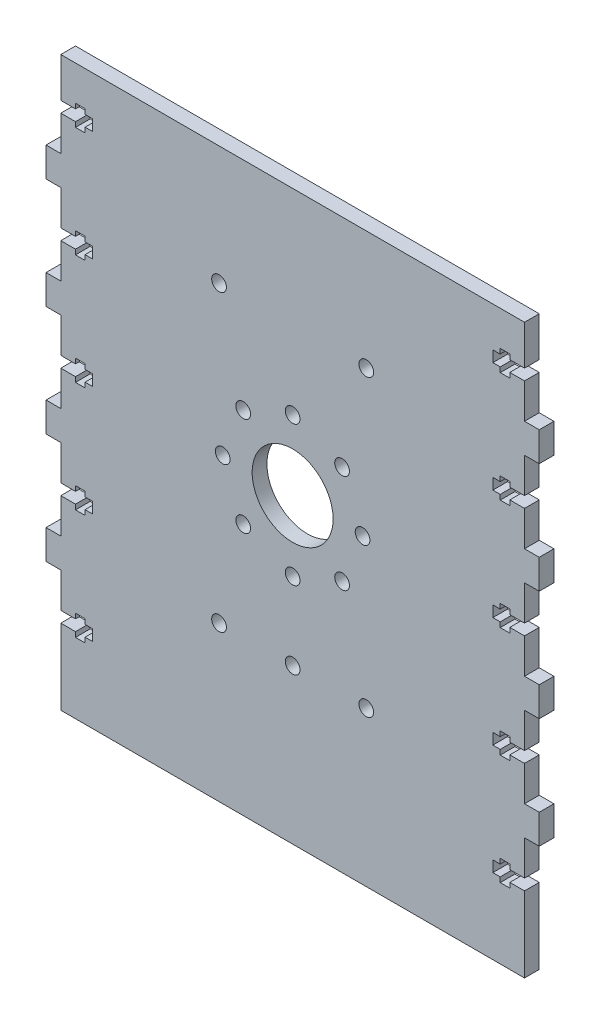
SolidWorks part; units mm, degrees
ref_plane "前视基准面" through (0, 0, 0) normal (0, 0, 1) x (1, 0, 0)
ref_plane "上视基准面" through (0, 0, 0) normal (0, 1, 0) x (1, 0, 0)
ref_plane "右视基准面" through (0, 0, 0) normal (1, 0, 0) x (0, 0, -1)
sketch "草图1" plane through (0, 0, 0) normal (0, 0, 1) x (1, 0, 0)
  line L9 (145, 46.5) -> (149, 46.5)
  line L10 (149, 46.5) -> (149, 45.15)
  line L11 (149, 45.15) -> (151.6, 45.15)
  line L12 (151.6, 45.15) -> (151.6, 46.5)
  line L13 (151.6, 46.5) -> (153.6, 46.5)
  line L14 (153.6, 46.5) -> (153.6, 49.5)
  line L23 (145, 48) -> (143.6922, 48) construction
  line L24 (145, 46.5) -> (145, 49.5) construction
  line L25 (151.6, 50.85) -> (151.6, 49.5)
  line L26 (149, 49.5) -> (149, 50.85)
  line L27 (151.6, 49.5) -> (153.6, 49.5)
  line L28 (149, 50.85) -> (151.6, 50.85)
  line L29 (145, 49.5) -> (149, 49.5)
  line L31 (145, 29) -> (141, 29)
  line L32 (141, 29) -> (141, 37)
  line L33 (141, 37) -> (145, 37)
  line L34 (145, 37) -> (145, 46.5)
  line L35 (141, 33) -> (142.703, 33) construction
  line L43 (149, 15.15) -> (151.6, 15.15)
  line L44 (151.6, 16.5) -> (153.6, 16.5)
  line L45 (149, 16.5) -> (149, 15.15)
  line L69 (262.4, 48) -> (153.6, 48) construction
  line L70 (151.6, 15.15) -> (151.6, 16.5)
  line L71 (153.6, 19.5) -> (153.6, 16.5)
  line L72 (151.6, 19.5) -> (153.6, 19.5)
  line L73 (151.6, 20.85) -> (151.6, 19.5)
  line L98 (149, 20.85) -> (151.6, 20.85)
  line L123 (149, 19.5) -> (149, 20.85)
  line L124 (145, 7) -> (145, 16.5)
  line L125 (149, 16.5) -> (145, 16.5)
  line L126 (149, 19.5) -> (145, 19.5)
  line L127 (145, 19.5) -> (145, 29)
  line L128 (153.6, 18) -> (150.6786, 18) construction
  line L129 (141, 3) -> (142.703, 3) construction
  line L130 (141, -1) -> (145, -1)
  line L131 (141, 7) -> (141, -1)
  line L132 (145, 7) -> (141, 7)
  line L133 (145, -1) -> (145, -10.5)
  line L134 (149, -10.5) -> (145, -10.5)
  line L135 (149, -13.5) -> (145, -13.5)
  line L136 (153.6, -12) -> (150.6786, -12) construction
  line L137 (149, -13.5) -> (149, -14.85)
  line L138 (149, -14.85) -> (151.6, -14.85)
  line L139 (151.6, -14.85) -> (151.6, -13.5)
  line L140 (151.6, -13.5) -> (153.6, -13.5)
  line L141 (153.6, -13.5) -> (153.6, -10.5)
  line L142 (151.6, -9.15) -> (151.6, -10.5)
  line L143 (149, -10.5) -> (149, -9.15)
  line L144 (151.6, -10.5) -> (153.6, -10.5)
  line L145 (149, -9.15) -> (151.6, -9.15)
  line L146 (153.6, 108) -> (150.6786, 108) construction
  line L147 (141, 93) -> (142.703, 93) construction
  line L148 (153.6, 78) -> (150.6786, 78) construction
  line L149 (141, 63) -> (142.703, 63) construction
  line L150 (145, 46.5) -> (149, 46.5)
  line L151 (149, 46.5) -> (149, 45.15)
  line L152 (149, 45.15) -> (151.6, 45.15)
  line L153 (151.6, 45.15) -> (151.6, 46.5)
  line L154 (151.6, 46.5) -> (153.6, 46.5)
  line L155 (151.6, 50.85) -> (151.6, 49.5)
  line L156 (149, 49.5) -> (149, 50.85)
  line L157 (151.6, 49.5) -> (153.6, 49.5)
  line L158 (145, 46.5) -> (149, 46.5)
  line L159 (149, 45.15) -> (151.6, 45.15)
  line L160 (151.6, 46.5) -> (153.6, 46.5)
  line L161 (149, 46.5) -> (149, 45.15)
  line L162 (151.6, 45.15) -> (151.6, 46.5)
  line L163 (151.6, 49.5) -> (153.6, 49.5)
  line L164 (151.6, 50.85) -> (151.6, 49.5)
  line L165 (149, 50.85) -> (151.6, 50.85)
  line L166 (149, 49.5) -> (149, 50.85)
  line L167 (145, 49.5) -> (149, 49.5)
  line L168 (149, 50.85) -> (151.6, 50.85)
  line L169 (145, 49.5) -> (149, 49.5)
  line L170 (149, 105.15) -> (151.6, 105.15)
  line L171 (151.6, 106.5) -> (153.6, 106.5)
  line L172 (149, 106.5) -> (149, 105.15)
  line L173 (151.6, 105.15) -> (151.6, 106.5)
  line L174 (153.6, 109.5) -> (153.6, 106.5)
  line L175 (151.6, 109.5) -> (153.6, 109.5)
  line L177 (151.6, 110.85) -> (151.6, 109.5)
  line L178 (149, 110.85) -> (151.6, 110.85)
  line L179 (149, 109.5) -> (149, 110.85)
  line L180 (149, 109.5) -> (145, 109.5)
  line L181 (149, 106.5) -> (145, 106.5)
  line L182 (145, 97) -> (145, 106.5)
  line L183 (145, 89) -> (141, 89)
  line L184 (141, 89) -> (141, 97)
  line L185 (141, 97) -> (145, 97)
  line L186 (145, 76.5) -> (145, 67)
  line L187 (149, 76.5) -> (145, 76.5)
  line L188 (149, 79.5) -> (145, 79.5)
  line L189 (145, 89) -> (145, 79.5)
  line L190 (149, 76.5) -> (149, 75.15)
  line L191 (149, 75.15) -> (151.6, 75.15)
  line L192 (151.6, 75.15) -> (151.6, 76.5)
  line L193 (151.6, 76.5) -> (153.6, 76.5)
  line L194 (153.6, 76.5) -> (153.6, 79.5)
  line L195 (151.6, 80.85) -> (151.6, 79.5)
  line L196 (149, 79.5) -> (149, 80.85)
  line L197 (151.6, 79.5) -> (153.6, 79.5)
  line L198 (149, 80.85) -> (151.6, 80.85)
  line L199 (145, 59) -> (145, 49.5)
  line L200 (141, 59) -> (145, 59)
  line L201 (141, 67) -> (141, 59)
  line L202 (145, 67) -> (141, 67)
  line L203 (145, 46.5) -> (149, 46.5)
  line L204 (149, 45.15) -> (151.6, 45.15)
  line L205 (151.6, 46.5) -> (153.6, 46.5)
  line L206 (149, 46.5) -> (149, 45.15)
  line L207 (151.6, 45.15) -> (151.6, 46.5)
  line L208 (151.6, 49.5) -> (153.6, 49.5)
  line L209 (151.6, 50.85) -> (151.6, 49.5)
  line L210 (149, 50.85) -> (151.6, 50.85)
  line L211 (149, 49.5) -> (149, 50.85)
  line L212 (145, 49.5) -> (149, 49.5)
  line L213 (275, 63) -> (273.297, 63) construction
  line L214 (262.4, 78) -> (265.3214, 78) construction
  line L215 (275, 93) -> (273.297, 93) construction
  line L216 (262.4, 108) -> (265.3214, 108) construction
  line L217 (262.4, -12) -> (265.3214, -12) construction
  line L218 (275, 3) -> (273.297, 3) construction
  line L219 (262.4, 18) -> (265.3214, 18) construction
  line L220 (275, 33) -> (273.297, 33) construction
  line L221 (271, 46.5) -> (271, 49.5) construction
  line L222 (271, 48) -> (272.3078, 48) construction
  line L223 (271, -27) -> (271, -13.5)
  line L224 (271, 123) -> (271, 109.5)
  line L225 (271, -27) -> (271, -34)
  line L227 (271, 49.5) -> (267, 49.5)
  line L228 (267, 49.5) -> (267, 50.85)
  line L229 (267, 50.85) -> (264.4, 50.85)
  line L230 (264.4, 50.85) -> (264.4, 49.5)
  line L231 (264.4, 49.5) -> (262.4, 49.5)
  line L232 (264.4, 45.15) -> (264.4, 46.5)
  line L233 (267, 46.5) -> (267, 45.15)
  line L234 (264.4, 46.5) -> (262.4, 46.5)
  line L235 (267, 45.15) -> (264.4, 45.15)
  line L253 (271, 46.5) -> (267, 46.5)
  line L254 (271, 67) -> (275, 67)
  line L255 (145, -27) -> (145, -34)
  line L256 (208, 48) -> (208, 8) construction
  line L257 (208, 8) -> (188, 8) construction
  line L258 (275, 67) -> (275, 59)
  line L259 (275, 59) -> (271, 59)
  line L260 (271, 59) -> (271, 49.5)
  line L261 (267, 80.85) -> (264.4, 80.85)
  line L262 (264.4, 79.5) -> (262.4, 79.5)
  line L263 (267, 79.5) -> (267, 80.85)
  line L264 (264.4, 80.85) -> (264.4, 79.5)
  line L265 (262.4, 76.5) -> (262.4, 79.5)
  line L267 (264.4, 76.5) -> (262.4, 76.5)
  line L269 (264.4, 75.15) -> (264.4, 76.5)
  line L270 (267, 75.15) -> (264.4, 75.15)
  line L272 (267, 76.5) -> (267, 75.15)
  line L273 (271, 89) -> (271, 79.5)
  line L274 (267, 79.5) -> (271, 79.5)
  line L275 (267, 76.5) -> (271, 76.5)
  line L277 (271, 76.5) -> (271, 67)
  line L278 (275, 97) -> (271, 97)
  line L279 (275, 89) -> (275, 97)
  line L280 (271, 89) -> (275, 89)
  line L281 (271, 97) -> (271, 106.5)
  line L282 (267, 106.5) -> (271, 106.5)
  line L283 (267, 109.5) -> (271, 109.5)
  line L284 (267, 109.5) -> (267, 110.85)
  line L285 (267, 110.85) -> (264.4, 110.85)
  line L286 (264.4, 110.85) -> (264.4, 109.5)
  line L287 (264.4, 109.5) -> (262.4, 109.5)
  line L288 (262.4, 109.5) -> (262.4, 106.5)
  line L289 (264.4, 105.15) -> (264.4, 106.5)
  line L290 (267, 106.5) -> (267, 105.15)
  line L291 (264.4, 106.5) -> (262.4, 106.5)
  line L292 (267, 105.15) -> (264.4, 105.15)
  line L293 (271, 49.5) -> (267, 49.5)
  line L294 (267, 50.85) -> (264.4, 50.85)
  line L295 (271, 49.5) -> (267, 49.5)
  line L296 (267, 49.5) -> (267, 50.85)
  line L298 (267, 50.85) -> (264.4, 50.85)
  line L299 (264.4, 50.85) -> (264.4, 49.5)
  line L300 (264.4, 49.5) -> (262.4, 49.5)
  line L301 (264.4, 45.15) -> (264.4, 46.5)
  line L302 (267, 46.5) -> (267, 45.15)
  line L303 (264.4, 46.5) -> (262.4, 46.5)
  line L304 (267, 45.15) -> (264.4, 45.15)
  line L305 (271, 46.5) -> (267, 46.5)
  line L306 (264.4, 49.5) -> (262.4, 49.5)
  line L307 (267, 49.5) -> (267, 50.85)
  line L308 (264.4, 50.85) -> (264.4, 49.5)
  line L309 (264.4, 46.5) -> (262.4, 46.5)
  line L310 (264.4, 45.15) -> (264.4, 46.5)
  line L312 (267, 45.15) -> (264.4, 45.15)
  line L314 (267, 46.5) -> (267, 45.15)
  line L315 (271, 46.5) -> (267, 46.5)
  line L317 (267, -9.15) -> (264.4, -9.15)
  line L320 (264.4, -10.5) -> (262.4, -10.5)
  line L321 (267, -10.5) -> (267, -9.15)
  line L322 (264.4, -9.15) -> (264.4, -10.5)
  line L323 (262.4, -13.5) -> (262.4, -10.5)
  line L324 (264.4, -13.5) -> (262.4, -13.5)
  line L325 (264.4, -14.85) -> (264.4, -13.5)
  line L326 (267, -14.85) -> (264.4, -14.85)
  line L327 (267, -13.5) -> (267, -14.85)
  line L328 (267, -13.5) -> (271, -13.5)
  line L329 (267, -10.5) -> (271, -10.5)
  line L330 (271, -1) -> (271, -10.5)
  line L331 (271, 7) -> (275, 7)
  line L332 (275, 7) -> (275, -1)
  line L333 (275, -1) -> (271, -1)
  line L334 (271, 19.5) -> (271, 29)
  line L335 (267, 19.5) -> (271, 19.5)
  line L336 (267, 16.5) -> (271, 16.5)
  line L337 (271, 7) -> (271, 16.5)
  line L338 (267, 19.5) -> (267, 20.85)
  line L339 (267, 20.85) -> (264.4, 20.85)
  line L340 (264.4, 20.85) -> (264.4, 19.5)
  line L341 (264.4, 19.5) -> (262.4, 19.5)
  line L342 (262.4, 19.5) -> (262.4, 16.5)
  line L343 (264.4, 15.15) -> (264.4, 16.5)
  line L344 (267, 16.5) -> (267, 15.15)
  line L345 (264.4, 16.5) -> (262.4, 16.5)
  line L346 (267, 15.15) -> (264.4, 15.15)
  line L347 (271, 37) -> (271, 46.5)
  line L348 (275, 37) -> (271, 37)
  line L349 (275, 29) -> (275, 37)
  line L350 (271, 29) -> (275, 29)
  line L351 (271, 49.5) -> (267, 49.5)
  line L352 (267, 50.85) -> (264.4, 50.85)
  line L353 (264.4, 49.5) -> (262.4, 49.5)
  line L354 (267, 49.5) -> (267, 50.85)
  line L355 (264.4, 50.85) -> (264.4, 49.5)
  line L356 (262.4, 46.5) -> (262.4, 49.5)
  line L357 (264.4, 46.5) -> (262.4, 46.5)
  line L358 (264.4, 45.15) -> (264.4, 46.5)
  line L359 (267, 45.15) -> (264.4, 45.15)
  line L360 (267, 46.5) -> (267, 45.15)
  line L361 (271, 46.5) -> (267, 46.5)
  line L362 (145, 123) -> (271, 123)
  line L363 (145, -34) -> (271, -34)
  line L592 (145, 123) -> (145, 109.5)
  line L594 (145, -27) -> (145, -13.5)
  circle A6 centre (208, 48) radius 19 construction
  circle A7 centre (208, 29) radius 2
  circle A15 centre (208, 48) radius 11
  circle A69 centre (188, 8) radius 2
  circle A70 centre (228, 8) radius 2
  circle A71 centre (228, 88) radius 2
  circle A72 centre (188, 88) radius 2
  circle A73 centre (208, 8) radius 2
  circle A74 centre (194.565, 34.565) radius 2
  circle A75 centre (189, 48) radius 2
  circle A76 centre (194.565, 61.435) radius 2
  circle A77 centre (208, 67) radius 2
  circle A78 centre (221.435, 61.435) radius 2
  circle A79 centre (227, 48) radius 2
  circle A80 centre (221.435, 34.565) radius 2
  point P15 (144.3461, 48)
  dimension "D2" = 40
  dimension "D7" = 38
  dimension "D1" = 15
  dimension "D9" = 63
  dimension "D3" = 4
  dimension "D4" = 2
  dimension "D5" = 2.6
  dimension "D6" = 1.35
  dimension "D8" = 1.5
  dimension "D10" = 40
extrude "凸台-拉伸1" add sketch "草图1" along normal blind 4 contours L594 L255 L363 L225 L223 L328 L327 L326 L325 L324 L323 L320 L322 L317 L321 L329 L330 L333 L332 L331 L337 L336 L344 L346 L343 L345 L342 L341 L340 L339 L338 L335 L334 L350 L349 L348 L347 L253 L233 L235 L232 L234 L356 L231 L230 L229 L228 L227 L260 L259 L258
sketch "草图2" plane through (271, 0, 0) normal (1, 0, 0) x (0, 0, -1)
  line L0 (-2, -10.5) -> (-2, -13.5)
  line L1 (-4, -10.5) -> (0, -10.5) construction
  line L2 (-4, -13.5) -> (0, -13.5) construction
  circle A0 centre (-2, -12) radius 1.5
sketch "草图3" plane through (0, 0, 4) normal (0, 0, 1) x (1, 0, 0)
  line L0 (271, 123) -> (271, 109.5) construction
  line L1 (145, 123) -> (271, 123)
  line L2 (145, 123) -> (145, 120.3)
  line L3 (145, 120.3) -> (271, 120.3)
  line L4 (271, 123) -> (271, 120.3)
  dimension "D1" = 2.7
extrude "切除-拉伸1" cut sketch "草图3" against normal blind 10
